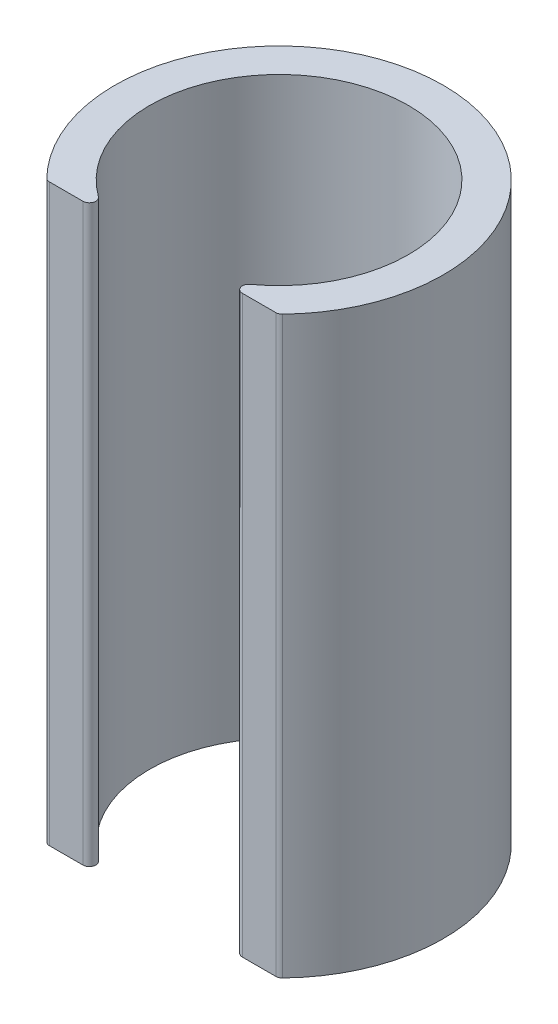
SolidWorks part; units mm, degrees
ref_plane "Front Plane" through (0, 0, 0) normal (0, 0, 1) x (1, 0, 0)
ref_plane "Top Plane" through (0, 0, 0) normal (0, 1, 0) x (1, 0, 0)
ref_plane "Right Plane" through (0, 0, 0) normal (1, 0, 0) x (0, 0, -1)
sketch "Sketch1" plane through (0, 0, 0) normal (0, 1, 0) x (1, 0, 0)
  line L0 (-2.1794, -4.5) -> (2.1794, -4.5) construction
  line L1 (-2.1794, -4.5) -> (-4.4802, -4.5)
  line L2 (2.1794, -4.5) -> (4.4802, -4.5)
  arc A0 (2.1794, -4.5) -> (-2.1794, -4.5) centre (0, 0) ccw
  arc A1 (-4.4802, -4.5) -> (4.4802, -4.5) centre (0, 0) cw
  dimension "D1" = 10
  dimension "D3" = 6.35
  dimension "D2" = 4.5
extrude "Boss-Extrude1" add sketch "Sketch1" along normal blind 22.225
fillet "Fillet1" radius 0.25 4 edges at (4.4802, 11.1125, 4.5) (2.1794, 11.1125, 4.5) (-4.4802, 11.1125, 4.5) (-2.1794, 11.1125, 4.5)
